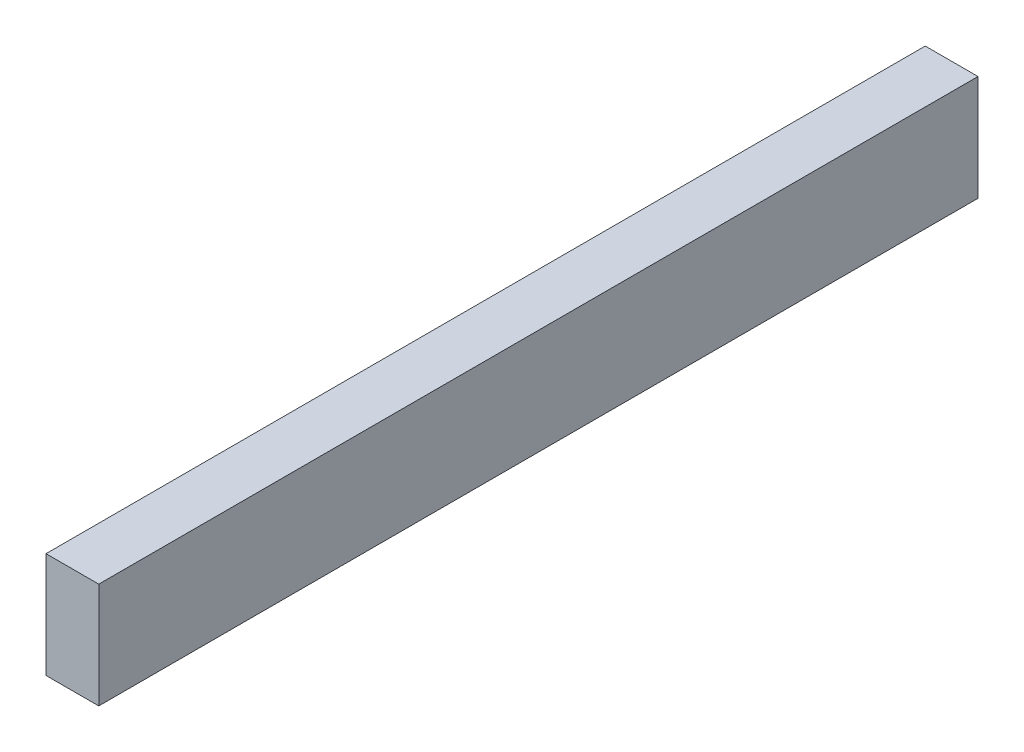
SolidWorks part; units mm, degrees
ref_plane "Front Plane" through (0, 0, 0) normal (0, 0, 1) x (1, 0, 0)
ref_plane "Top Plane" through (0, 0, 0) normal (0, 1, 0) x (1, 0, 0)
ref_plane "Right Plane" through (0, 0, 0) normal (1, 0, 0) x (0, 0, -1)
sketch "Sketch1" plane through (0, 0, 0) normal (0, 0, 1) x (1, 0, 0)
  line L1 (-15, -30) -> (15, -30)
  line L2 (-15, -30) -> (-15, 30)
  line L3 (-15, 30) -> (15, 30)
  line L4 (15, -30) -> (15, 30)
  line L5 (-15, -30) -> (15, 30) construction
  line L6 (-15, 30) -> (15, -30) construction
  point P0 (0, 0)
  dimension "D1" = 60
  dimension "D2" = 30
extrude "Boss-Extrude1" add sketch "Sketch1" along normal mid plane 500
